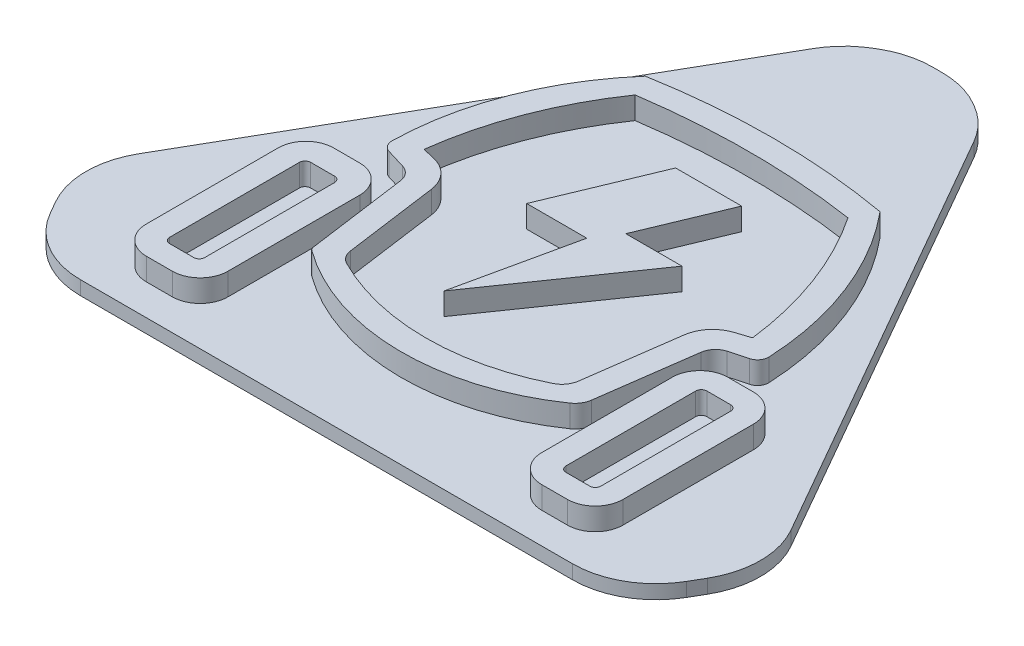
SolidWorks part; units mm, degrees
ref_plane "Alzado" through (0, 0, 0) normal (0, 0, 1) x (1, 0, 0)
ref_plane "Planta" through (0, 0, 0) normal (0, 1, 0) x (1, 0, 0)
ref_plane "Vista lateral" through (0, 0, 0) normal (1, 0, 0) x (0, 0, -1)
sketch "Croquis1" plane through (0, 0, 0) normal (0, 1, 0) x (1, 0, 0)
  line L0 (87.6315, 310.5211) -> (567.6315, 310.5211) construction
  line L1 (32.5024, 10.3178) -> (29.3069, 9.4425)
  line L2 (24.7353, -10.3642) -> (27.1277, 6.9595)
  line L3 (20.6033, -8.5709) -> (22.9064, 8.1064)
  line L4 (29.512, 13.8171) -> (26.9803, 12.9868)
  line L5 (-29.3614, 13.6303) -> (-27.0648, 13.0936)
  line L6 (-20.1613, -8.8301) -> (-22.4864, 8.0689)
  line L7 (-32.1505, 10.151) -> (-28.6939, 9.1014)
  line L8 (-24.091, -11.5505) -> (-26.5935, 6.6397)
  line L9 (-5.5081, -6.599) -> (12.0027, 18.6338)
  line L10 (12.0027, 18.6338) -> (1.9049, 18.6338)
  line L11 (1.9049, 18.6338) -> (8.0152, 33.3476)
  line L12 (8.0152, 33.3476) -> (-3.8483, 33.3476)
  line L13 (-3.8483, 33.3476) -> (-11.706, 14.4261)
  line L14 (-11.706, 14.4261) -> (-0.899, 14.4261)
  line L15 (-0.899, 14.4261) -> (-5.5081, -6.599)
  line L17 (33.4315, -27.9901) -> (38.0306, -27.9901)
  line L18 (28.4315, -22.9901) -> (28.4315, 0.4578)
  line L19 (33.4315, 5.4578) -> (38.0306, 5.4578)
  line L20 (43.0306, -22.9901) -> (43.0306, 0.4578)
  line L21 (33.681, -23.9094) -> (37.9695, -23.9094)
  line L22 (32.681, -22.9094) -> (32.681, 0.4293)
  line L23 (33.681, 1.4293) -> (37.9695, 1.4293)
  line L24 (38.9695, -22.9094) -> (38.9695, 0.4293)
  line L25 (-33.0182, -27.9708) -> (-37.7038, -27.9708)
  line L26 (-28.0182, -22.9708) -> (-28.0182, 0.7254)
  line L27 (-33.0182, 5.7254) -> (-37.7038, 5.7254)
  line L28 (-42.7038, -22.9708) -> (-42.7038, 0.7254)
  line L29 (-37.5426, 1.4145) -> (-33.2302, 1.4145)
  line L30 (-38.5426, 0.4145) -> (-38.5426, -22.9217)
  line L31 (-37.5426, -23.9217) -> (-33.2302, -23.9217)
  line L32 (-32.2302, 0.4145) -> (-32.2302, -22.9217)
  circle A0 centre (0, 0) radius 50
  arc A1 (-20.8633, 44.9103) -> (21.3414, 44.9103) centre (0.2391, -74.0383) cw
  arc A2 (21.3414, 44.9103) -> (33.9718, 12.3402) centre (-20.9641, 9.7706) cw
  arc A3 (-20.8633, 44.9103) -> (-33.5691, 12.1033) centre (17.6898, 11.1152) ccw
  arc A4 (-18.8596, 41.0749) -> (19.4073, 41.0749) centre (0.2738, -87.0342) cw
  arc A5 (19.4073, 41.0749) -> (29.512, 13.8171) centre (-32.3959, 6.3692) cw
  arc A6 (-18.8596, 41.0749) -> (-29.3614, 13.6303) centre (31.9534, 5.8994) ccw
  arc A7 (-18.5462, -11.0968) -> (18.6979, -11.2244) centre (0.2027, 25.8724) ccw
  arc A8 (23.2567, -12.7657) -> (-23.6873, -12.2238) centre (0.1676, 20.678) cw
  arc A9 (-26.5935, 6.6397) -> (-28.6939, 9.1014) centre (-29.5655, 6.2308) ccw
  arc A10 (27.1277, 6.9595) -> (29.3069, 9.4425) centre (30.0995, 6.5491) cw
  arc A11 (22.9064, 8.1064) -> (26.9803, 12.9868) centre (28.85, 7.2856) cw
  arc A12 (-22.4864, 8.0689) -> (-27.0648, 13.0936) centre (-28.4304, 7.251) ccw
  arc A13 (-33.5691, 12.1033) -> (-32.1505, 10.151) centre (-31.5695, 12.0647) ccw
  arc A14 (33.9718, 12.3402) -> (32.5024, 10.3178) centre (31.974, 12.2468) cw
  arc A15 (-37.7038, -27.9708) -> (-42.7038, -22.9708) centre (-37.7038, -22.9708) cw
  arc A16 (-37.7038, 5.7254) -> (-42.7038, 0.7254) centre (-37.7038, 0.7254) ccw
  arc A17 (-28.0182, 0.7254) -> (-33.0182, 5.7254) centre (-33.0182, 0.7254) ccw
  arc A18 (-33.0182, -27.9708) -> (-28.0182, -22.9708) centre (-33.0182, -22.9708) ccw
  arc A19 (33.4315, -27.9901) -> (28.4315, -22.9901) centre (33.4315, -22.9901) cw
  arc A20 (38.0306, -27.9901) -> (43.0306, -22.9901) centre (38.0306, -22.9901) ccw
  arc A21 (33.4315, 5.4578) -> (28.4315, 0.4578) centre (33.4315, 0.4578) ccw
  arc A22 (43.0306, 0.4578) -> (38.0306, 5.4578) centre (38.0306, 0.4578) ccw
  arc A23 (-37.5426, 1.4145) -> (-38.5426, 0.4145) centre (-37.5426, 0.4145) ccw
  arc A24 (-33.2302, 1.4145) -> (-32.2302, 0.4145) centre (-33.2302, 0.4145) cw
  arc A25 (-38.5426, -22.9217) -> (-37.5426, -23.9217) centre (-37.5426, -22.9217) ccw
  arc A26 (-33.2302, -23.9217) -> (-32.2302, -22.9217) centre (-33.2302, -22.9217) ccw
  arc A27 (37.9695, -23.9094) -> (38.9695, -22.9094) centre (37.9695, -22.9094) ccw
  arc A28 (37.9695, 1.4293) -> (38.9695, 0.4293) centre (37.9695, 0.4293) cw
  arc A29 (33.681, -23.9094) -> (32.681, -22.9094) centre (33.681, -22.9094) cw
  arc A30 (32.681, 0.4293) -> (33.681, 1.4293) centre (33.681, 0.4293) cw
  arc A31 (-24.091, -11.5505) -> (-23.6873, -12.2238) centre (-23.1003, -11.4142) ccw
  arc A32 (-20.1613, -8.8301) -> (-18.5462, -11.0968) centre (-17.1893, -8.4212) ccw
  arc A33 (20.6033, -8.5709) -> (18.6979, -11.2244) centre (17.1362, -8.0921) cw
  arc A34 (24.7353, -10.3642) -> (23.2567, -12.7657) centre (21.2682, -9.8854) cw
  circle A35 centre (0, 0) radius 55
  dimension "D1" = 3
  dimension "D2" = 6
  dimension "D3" = 2
  dimension "D4" = 2
  dimension "D5" = 5
  dimension "D6" = 1
  dimension "D7" = 1
  dimension "D8" = 3
  dimension "D9" = 3.5
  dimension "D10" = 3.5
extrude "Saliente-Extruir1" add sketch "Croquis1" along normal blind 4 contours A34 L2 A10 L1 A14 A2 A1 A3 A13 L7 A9 L8 A31 A8 L3 A33 A7 A32 L6 A12 L5 A6 A4 A5 L4 A11 | L14 L15 L9 L10 L11 L12 L13 | L25 A18 L26 A17 L27 A16 L28 A15 A26 L31 A25 L30 A23 L29 A24 L32 | L20 A22 L19 A21 L18 A19 L17 A20 L22 A30 L23 A28 L24 A27 L21 A29
sketch "Croquis2" plane through (0, 0, 0) normal (0, -1, 0) x (1, 0, 0)
  line L1 (0, 50) -> (22.9129, 50)
  line L2 (22.9129, 47) -> (-22.9129, 47)
  line L4 (0, -50) -> (22.9129, -50)
  line L5 (22.9129, -53) -> (-22.9129, -53)
  arc A0 (22.9129, -53) -> (22.9129, 47) centre (0, -3) ccw
  arc A1 (-22.9129, 47) -> (-22.9129, -53) centre (0, -3) ccw
sketch "Croquis4" plane through (0, 0, 0) normal (0, -1, 0) x (1, 0, 0)
  line L0 (-43.9467, 33.5504) -> (44.5097, 33.5504)
  line L1 (58.9204, 8.694) -> (14.8309, -68.3115)
  line L2 (-14.0565, -68.3335) -> (-58.3233, 8.7091)
  line L3 (1.3132, -76.1554) -> (-0.5268, -76.1568)
  line L4 (57.4866, 26.0738) -> (58.8799, 23.6705)
  line L5 (-58.2999, 23.6955) -> (-56.9292, 26.0639)
  line L6 (-8.0468, -74.1423) -> (-8.5591, -73.846)
  line L7 (9.3419, -73.8324) -> (8.8301, -74.1294)
  arc A0 (58.8799, 23.6705) -> (58.9204, 8.694) centre (45.9031, 16.1471) cw
  arc A1 (57.4866, 26.0738) -> (44.5097, 33.5504) centre (44.5097, 18.5504) ccw
  arc A2 (-56.9292, 26.0639) -> (-43.9467, 33.5504) centre (-43.9467, 18.5504) cw
  arc A3 (-58.2999, 23.6955) -> (-58.3233, 8.7091) centre (-45.3173, 16.182) ccw
  arc A4 (9.3419, -73.8324) -> (14.8309, -68.3115) centre (1.8136, -60.8584) ccw
  arc A5 (-8.5591, -73.846) -> (-14.0565, -68.3335) centre (-1.0505, -60.8606) cw
  arc A6 (-0.5268, -76.1568) -> (-8.0468, -74.1423) centre (-0.5383, -61.1568) cw
  arc A7 (1.3132, -76.1554) -> (8.8301, -74.1294) centre (1.3017, -61.1554) ccw
  point P0 (-72.5965, 33.5504)
  point P1 (73.152, 33.5504)
  point P2 (10.3438, -76.1486)
  point P3 (0.4064, -93.505)
  point P4 (-9.5575, -76.1637)
  point P11 (63.2145, 16.1939)
  point P14 (53.152, 33.5504)
  point P17 (-52.5965, 33.5504)
  point P20 (-62.6326, 16.2091)
  point P27 (12.8282, -71.8094)
  point P30 (-12.0485, -71.8284)
  point P33 (-4.5575, -76.1599)
  point P36 (5.3438, -76.1524)
  dimension "D1" = 15
  dimension "D2" = 15
extrude "Saliente-Extruir4" add sketch "Croquis4" along normal blind 2.5
